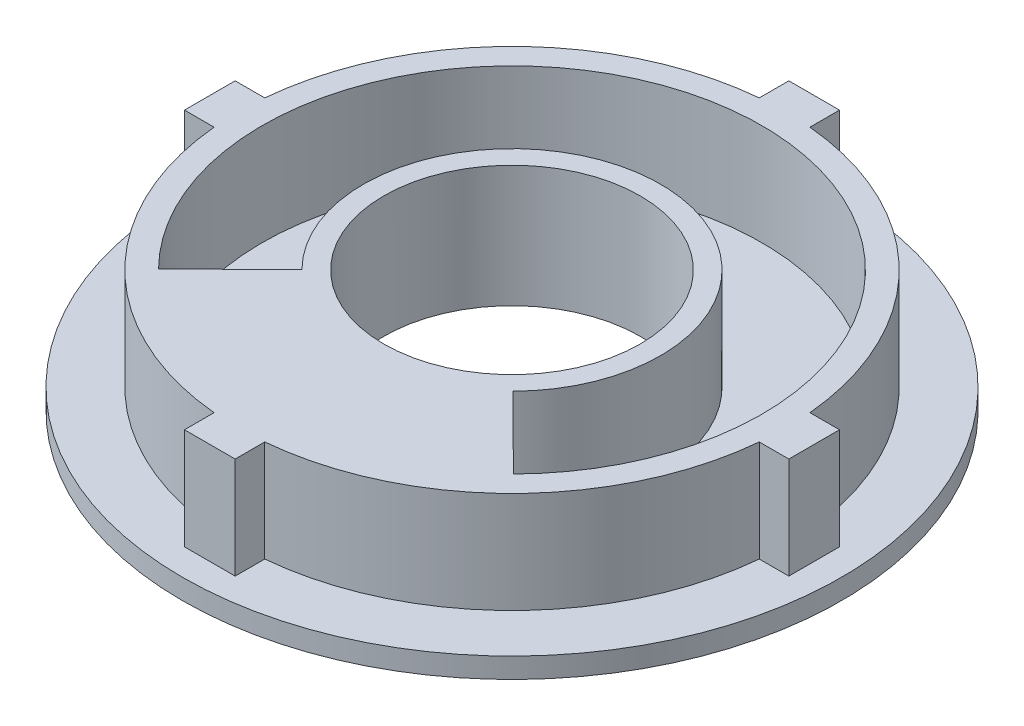
SolidWorks part; units mm, degrees
ref_plane "Front Plane" through (0, 0, 0) normal (0, 0, 1) x (1, 0, 0)
ref_plane "Top Plane" through (0, 0, 0) normal (0, 1, 0) x (1, 0, 0)
ref_plane "Right Plane" through (0, 0, 0) normal (1, 0, 0) x (0, 0, -1)
sketch "Sketch1" plane through (0, 0, 0) normal (0, 1, 0) x (1, 0, 0)
  line L0 (-17.5, -17.3601) -> (-10.4006, -10.3175)
  line L1 (0, -6.6) -> (0, 6.6) construction
  line L2 (17.5, -17.3601) -> (10.4006, -10.3175)
  line L4 (-17.5, -17.3601) -> (3.5272, -38.5567) construction
  circle A0 centre (0, 0) radius 27
  arc A1 (10.4006, -10.3175) -> (-10.4006, -10.3175) centre (0, 0) ccw
  arc A2 (17.5, -17.3601) -> (-17.5, -17.3601) centre (0, 0) ccw
  circle A3 centre (0, 0) radius 12.65
  arc A4 (16.047, 11.8457) -> (13.9503, -13.8388) centre (0.18, 0.2132) cw construction
  circle A5 centre (0, 0) radius 19.9533 construction
  dimension "D1" = 54
  dimension "D2" = 2.35
  dimension "D3" = 10
  dimension "D4" = 2
  dimension "D5" = 35
extrude "Boss-Extrude1" add sketch "Sketch1" along normal blind 10
sketch "Sketch2" plane through (0, 0, 0) normal (0, -1, 0) x (1, 0, 0)
  circle A0 centre (0, 0) radius 32.5
  circle A1 centre (0, 0) radius 12.65
  circle A2 centre (0, 0) radius 12.65 construction
  dimension "D1" = 65
extrude "Boss-Extrude2" add sketch "Sketch2" along normal blind 2
sketch "Sketch3" plane through (0, 0, 0) normal (0, 1, 0) x (1, 0, 0)
  line L0 (0, -6.6) -> (0, 6.6) construction
  line L1 (-2.5, 29.8) -> (2.5, 29.8)
  line L2 (-2.5, 29.8) -> (-2.5, 25.4032)
  line L3 (-2.5, 25.4032) -> (2.5, 25.4032)
  line L4 (2.5, 29.8) -> (2.5, 25.4032)
  line L5 (-2.5, 29.8) -> (2.5, 25.4032) construction
  line L6 (-2.5, 25.4032) -> (2.5, 29.8) construction
  line L7 (29.8, 2.5) -> (25.4032, 2.5)
  line L8 (29.8, 2.5) -> (29.8, -2.5)
  line L9 (29.8, -2.5) -> (25.4032, -2.5)
  line L10 (25.4032, 2.5) -> (25.4032, -2.5)
  line L11 (2.5, -29.8) -> (2.5, -25.4032)
  line L12 (2.5, -29.8) -> (-2.5, -29.8)
  line L13 (-2.5, -29.8) -> (-2.5, -25.4032)
  line L14 (2.5, -25.4032) -> (-2.5, -25.4032)
  line L15 (-29.8, -2.5) -> (-25.4032, -2.5)
  line L16 (-29.8, -2.5) -> (-29.8, 2.5)
  line L17 (-29.8, 2.5) -> (-25.4032, 2.5)
  line L18 (-25.4032, -2.5) -> (-25.4032, 2.5)
  circle A1 centre (0, 0) radius 27 construction
  point P0 (0, 27.6016)
  dimension "D2" = 29.8
  dimension "D1" = 5
  dimension "D3" = 4
extrude "Boss-Extrude3" add sketch "Sketch3" along normal blind 10
